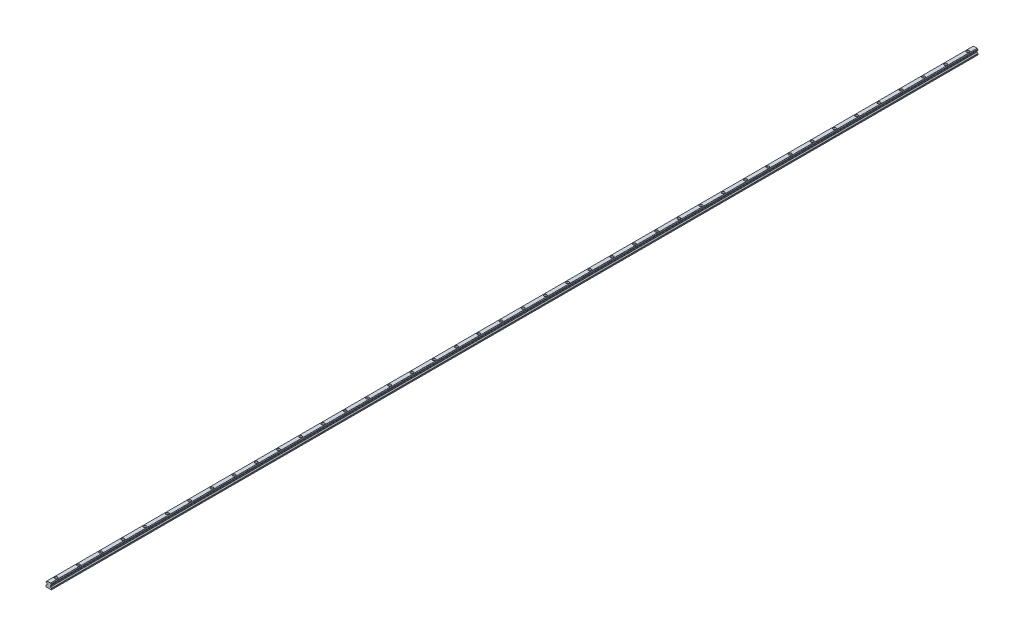
SolidWorks part; units mm, degrees
material "Plain Carbon Steel"
ref_plane "Front Plane" through (0, 0, 0) normal (0, 0, 1) x (1, 0, 0)
ref_plane "Top Plane" through (0, 0, 0) normal (0, 1, 0) x (1, 0, 0)
ref_plane "Right Plane" through (0, 0, 0) normal (1, 0, 0) x (0, 0, -1)
sketch "Rail Profile" plane through (0, 0, 0) normal (0, 0, 1) x (1, 0, 0)
  line L47 (0, 0) -> (0, 20) construction
  line L48 (-7, 0) -> (7, 0)
  line L49 (7, 0) -> (7.5, 0.5)
  line L50 (7.5, 0.5) -> (7.5, 3.0858)
  line L58 (7.2071, 3.7929) -> (4.8672, 6.1328)
  line L59 (4.75, 6.4157) -> (4.75, 8.5843)
  line L60 (4.8672, 8.8672) -> (5.063, 9.063)
  line L61 (7.5, 11.6657) -> (7.5, 12.3343)
  line L62 (-7, 0) -> (-7.5, 0.5)
  line L63 (5, 15) -> (-5, 15)
  line L64 (6.75, 9) -> (6.75, 15) construction
  line L65 (5.063, 14.937) -> (5, 15)
  line L66 (-7.5, 0.5) -> (-7.5, 3.0858)
  line L67 (6.75, 15) -> (3.75, 12) construction
  line L68 (3.75, 12) -> (6.75, 9) construction
  line L69 (7.1, 12.3343) -> (7.1, 11.6657) construction
  line L70 (6.4042, 13.0301) -> (6.4042, 10.9699) construction
  line L71 (-7.2071, 3.7929) -> (-4.8672, 6.1328)
  line L72 (-4.75, 6.4157) -> (-4.75, 8.5843)
  line L73 (-4.8672, 8.8672) -> (-5.063, 9.063)
  line L74 (5, 15) -> (8, 12) construction
  line L75 (4.8672, 8.8672) -> (8, 12) construction
  line L76 (-7.5, 11.6657) -> (-7.5, 12.3343)
  line L77 (-5.063, 14.937) -> (-5, 15)
  arc A4 (6.4734, 13.4241) -> (5.1741, 14.7234) centre (6.75, 15) cw
  arc A6 (5.1741, 9.2766) -> (6.4734, 10.5759) centre (6.75, 9) cw
  arc A7 (7.2071, 3.7929) -> (7.5, 3.0858) centre (6.5, 3.0858) cw
  arc A8 (5.063, 14.937) -> (5.1741, 14.7234) centre (4.7801, 14.6542) cw
  arc A9 (6.4734, 13.4241) -> (6.8012, 13.0792) centre (6.4042, 13.0301) cw
  arc A10 (7.1491, 12.7313) -> (7.5, 12.3343) centre (7.1, 12.3343) cw
  arc A11 (7.5, 11.6657) -> (7.1491, 11.2687) centre (7.1, 11.6657) cw
  arc A12 (6.8012, 10.9208) -> (6.4734, 10.5759) centre (6.4042, 10.9699) cw
  arc A13 (5.1741, 9.2766) -> (5.063, 9.063) centre (4.7801, 9.3458) cw
  arc A14 (4.8672, 8.8672) -> (4.75, 8.5843) centre (5.15, 8.5843) ccw
  arc A15 (4.75, 6.4157) -> (4.8672, 6.1328) centre (5.15, 6.4157) ccw
  arc A16 (6.8012, 13.0792) -> (7.1491, 12.7313) centre (7.1981, 13.1283) ccw
  arc A17 (7.1491, 11.2687) -> (6.8012, 10.9208) centre (7.1981, 10.8717) ccw
  arc A18 (-7.2071, 3.7929) -> (-7.5, 3.0858) centre (-6.5, 3.0858) ccw
  arc A19 (-4.75, 6.4157) -> (-4.8672, 6.1328) centre (-5.15, 6.4157) cw
  arc A20 (-4.8672, 8.8672) -> (-4.75, 8.5843) centre (-5.15, 8.5843) cw
  arc A21 (-5.1741, 9.2766) -> (-5.063, 9.063) centre (-4.7801, 9.3458) ccw
  arc A22 (-5.1741, 9.2766) -> (-6.4734, 10.5759) centre (-6.75, 9) ccw
  arc A23 (-6.8012, 10.9208) -> (-6.4734, 10.5759) centre (-6.4042, 10.9699) ccw
  arc A24 (-7.1491, 11.2687) -> (-6.8012, 10.9208) centre (-7.1981, 10.8717) cw
  arc A25 (-7.5, 11.6657) -> (-7.1491, 11.2687) centre (-7.1, 11.6657) ccw
  arc A26 (-7.1491, 12.7313) -> (-7.5, 12.3343) centre (-7.1, 12.3343) ccw
  arc A27 (-6.8012, 13.0792) -> (-7.1491, 12.7313) centre (-7.1981, 13.1283) cw
  arc A28 (-6.4734, 13.4241) -> (-6.8012, 13.0792) centre (-6.4042, 13.0301) ccw
  arc A29 (-6.4734, 13.4241) -> (-5.1741, 14.7234) centre (-6.75, 15) ccw
  arc A30 (-5.063, 14.937) -> (-5.1741, 14.7234) centre (-4.7801, 14.6542) ccw
  point P2 (4.75, 7.5)
  point P12 (7.5, 12)
  point P19 (6.75, 12)
  point P25 (5.1578, 14.8422)
  point P50 (8, 12)
  point P78 (0, 15)
  dimension "Rb" = 1.6
  dimension "Rf1" = 1
  dimension "Rf2" = 0.4
  dimension "WR" = 15
  dimension "Wi" = 9.5
  dimension "Wt" = 5
  dimension "Ac" = 135
  dimension "HR" = 15
  dimension "Hm" = 7.5
  dimension "Hb" = 12
  dimension "Hc" = 0.5
  dimension "Wb" = 7.5
extrude "Body" add sketch "Rail Profile" against normal blind 2500
chamfer "Aesthetic Chamfer" distance 0.15 angle 45 84 edges at (-5.0315, 14.9685, 0) (-5.135, 14.8388, 0) (-5.6186, 13.8686, 0) (-6.6941, 13.3057, 0) (-6.9153, 12.8454, 0) (-7.3997, 12.5992, 0) (-7.5, 12, 0) (-7.3997, 11.4008, 0) (-6.9153, 11.1546, 0) (-6.6941, 10.6943, 0) (-5.6186, 10.1314, 0) (-5.135, 9.1612, 0) (-4.9651, 8.9651, 0) (-4.7804, 8.7374, 0) (-4.75, 7.5, 0) (-4.7804, 6.2626, 0) (-6.0371, 4.9629, 0) (-7.4239, 3.4685, 0) (-7.5, 1.7929, 0) (-7.25, 0.25, 0) (0, 0, 0) (7.25, 0.25, 0) (5.0315, 14.9685, 0) (5.135, 14.8388, 0) (5.6186, 13.8686, 0) (6.6941, 13.3057, 0) (6.9153, 12.8454, 0) (7.3997, 12.5992, 0) (7.5, 12, 0) (7.3997, 11.4008, 0) (6.9153, 11.1546, 0) (6.6941, 10.6943, 0) (5.6186, 10.1314, 0) (5.135, 9.1612, 0) (4.9651, 8.9651, 0) (4.7804, 8.7374, 0) (7.5, 1.7929, 0) (4.75, 7.5, 0) (7.4239, 3.4685, 0) (4.7804, 6.2626, 0) (6.0371, 4.9629, 0) (0, 15, 0) (5.0315, 14.9685, -2500) (5.135, 14.8388, -2500) (5.6186, 13.8686, -2500) (6.6941, 13.3057, -2500) (6.9153, 12.8454, -2500) (7.3997, 12.5992, -2500) (7.5, 12, -2500) (7.3997, 11.4008, -2500) (6.9153, 11.1546, -2500) (6.6941, 10.6943, -2500) (5.6186, 10.1314, -2500) (5.135, 9.1612, -2500) (4.9651, 8.9651, -2500) (4.7804, 8.7374, -2500) (4.75, 7.5, -2500) (4.7804, 6.2626, -2500) (6.0371, 4.9629, -2500) (7.4239, 3.4685, -2500) (7.5, 1.7929, -2500) (7.25, 0.25, -2500) (0, 0, -2500) (-7.25, 0.25, -2500) (-5.0315, 14.9685, -2500) (-5.135, 14.8388, -2500) (-5.6186, 13.8686, -2500) (-6.6941, 13.3057, -2500) (-6.9153, 12.8454, -2500) (-7.3997, 12.5992, -2500) (-7.5, 12, -2500) (-7.3997, 11.4008, -2500) (-6.9153, 11.1546, -2500) (-6.6941, 10.6943, -2500) (-5.6186, 10.1314, -2500) (-7.5, 1.7929, -2500) (-5.135, 9.1612, -2500) (-7.4239, 3.4685, -2500) (-4.9651, 8.9651, -2500) (-6.0371, 4.9629, -2500) (-4.7804, 8.7374, -2500) (-4.7804, 6.2626, -2500) (-4.75, 7.5, -2500) (0, 15, -2500)
hole_wizard "Mounting Hole" positions "3DSketch1" profile "Sketch1" counterbore size "M4" standard "ISO" end condition through all
sketch3d "3DSketch1"
  point P0 (0, 15, -20)
  dimension "D1" = 7.5
  dimension "E1" = 20
sketch "Sketch1" plane through (0, 15, -20) normal (1, 0, 0) x (0, 0, 1)
  line L0 (0, 0) -> (0, 15)
  line L1 (2.25, 14.9) -> (2.35, 15)
  line L2 (2.25, 14.9) -> (2.25, 5.4)
  line L3 (2.25, 5.4) -> (2.35, 5.3)
  line L4 (2.35, 5.3) -> (3.75, 5.3)
  line L5 (3.75, 5.3) -> (3.75, 0.1)
  line L6 (3.75, 0.1) -> (3.85, 0)
  line L7 (3.85, 0) -> (0, 0)
  line L8 (-3.75, 0.1) -> (-3.85, 0) construction
  line L9 (-2.25, 5.4) -> (-2.35, 5.3) construction
  line L11 (0, -6.35) -> (0, 107.95) construction
  line L12 (2.35, 15) -> (0, 15)
  line L13 (-2.25, 14.9) -> (-2.35, 15) construction
  dimension "Thru Hole Dia." = 4.5
  dimension "Thru Hole Depth" = 15
  dimension "C'Bore Dia." = 7.5
  dimension "C'Bore Depth" = 5.3
  dimension "Near C'Sink Dia." = 7.7
  dimension "Near C'Sink Angle" = 90
  dimension "Mid C'Sink Dia." = 4.7
  dimension "Mid C'Sink Angle" = 90
  dimension "Far C'Sink Dia." = 4.7
  dimension "Far C'Sink Angle" = 90
fillet "Production Fillet" radius 0.1 1 edges at (0, 9.7, -16.25)
pattern_linear "Mounting Holes Pattern" count 42 spacing 60 along (0, 0, -1) of "Mounting Hole", "Production Fillet"
equation "\"Wt@Rail Profile\"= \"WR@Rail Profile\" / 3'Top Side Half Width"
equation "\"Hm@Rail Profile\"= \"HR@Rail Profile\" / 2'Recirculation Avoidance Height"
equation "\"Hb@Rail Profile\"= 0.8 * \"HR@Rail Profile\"'Pivot Height"
equation "\"Hc@Rail Profile\"= \"WR@Rail Profile\" / 30'Chamfer Width"
equation "\"Wb@Rail Profile\"= \"WR@Rail Profile\" / 2'Ball Center Cross Width"
equation "\"D1@3DSketch1\"= \"WR@Rail Profile\" / 2'Hole Center Position"
